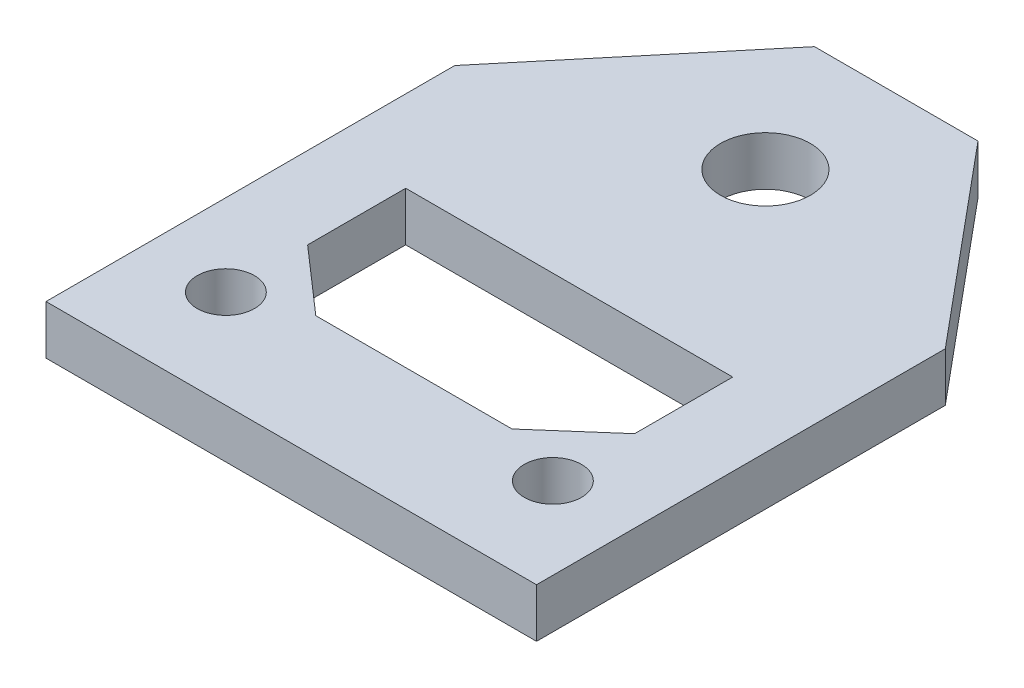
SolidWorks part; units mm, degrees
ref_plane "前视基准面" through (0, 0, 0) normal (0, 0, 1) x (1, 0, 0)
ref_plane "上视基准面" through (0, 0, 0) normal (0, 1, 0) x (1, 0, 0)
ref_plane "右视基准面" through (0, 0, 0) normal (1, 0, 0) x (0, 0, -1)
sketch "草图2" plane through (0, 0, 0) normal (0, 1, 0) x (1, 0, 0)
  line L0 (-10, 17) -> (10, 17)
  line L2 (-15, 25) -> (-15, 0)
  line L3 (-15, 0) -> (15, 0)
  line L4 (15, 25) -> (15, 0)
  line L5 (0, 37) -> (0, 0) construction
  line L7 (-5, 37) -> (-15, 25)
  line L9 (5, 37) -> (15, 25)
  line L13 (-10, 17) -> (-10, 11)
  line L15 (10, 17) -> (10, 11)
  line L18 (-5, 37) -> (5, 37)
  line L19 (-10, 11) -> (-6, 7.5)
  line L20 (-6, 7.5) -> (6, 7.5)
  line L21 (6, 7.5) -> (10, 11)
  circle A0 centre (-10, 6) radius 1.75
  circle A1 centre (10, 6) radius 1.75
  circle A4 centre (0, 29) radius 2.75
  point P15 (0, 7.5)
  point P28 (0, 17)
  dimension "D2" = 3.5
  dimension "D4" = 30
  dimension "D5" = 1.5
  dimension "D6" = 10
  dimension "D9" = 12
  dimension "D11" = 5.5
  dimension "D1" = 20
  dimension "D3" = 25
  dimension "D7" = 6
  dimension "D8" = 20
  dimension "D10" = 6
  dimension "D12" = 17
  dimension "D13" = 8
  dimension "D14" = 37
extrude "凸台-拉伸2" add sketch "草图2" against normal blind 3
